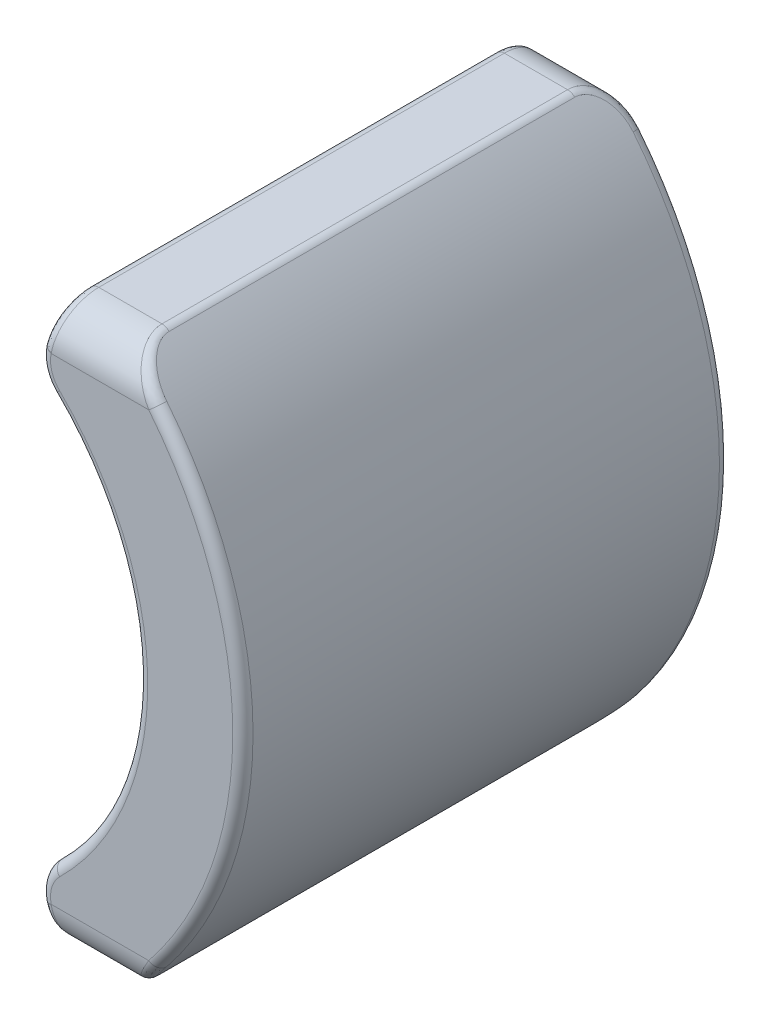
SolidWorks part; units mm, degrees
ref_plane "Front Plane" through (0, 0, 0) normal (0, 0, 1) x (1, 0, 0)
ref_plane "Top Plane" through (0, 0, 0) normal (0, 1, 0) x (1, 0, 0)
ref_plane "Right Plane" through (0, 0, 0) normal (1, 0, 0) x (0, 0, -1)
sketch "Sketch1" plane through (0, 0, 0) normal (0, 0, 1) x (1, 0, 0)
  line L0 (0, 0) -> (-9.63, 0) construction
  line L1 (-2.8919, -6.88) -> (-4.7519, -6.88)
  line L2 (-4.7519, -6.88) -> (-5.0982, -5.38)
  line L3 (-4.7519, 6.88) -> (-5.0982, 5.38)
  line L4 (-2.8919, 6.88) -> (-4.7519, 6.88)
  arc A0 (-2.8919, -6.88) -> (-2.8919, 6.88) centre (-9.63, 0) ccw
  arc A1 (-5.0982, 5.38) -> (-5.0982, -5.38) centre (-9.63, 0) cw
  point P6 (0, 0)
  dimension "D1" = 9.63
  dimension "D2" = 6.88
  dimension "D3" = 103
  dimension "D4" = 1.86
  dimension "D5" = 1.5
extrude "Boss-Extrude1" add sketch "Sketch1" along normal blind 12
fillet "Fillet1" radius 1 2 edges at (-5.0982, 5.38, 6) (-5.0982, -5.38, 6)
fillet "Fillet2" radius 1 4 edges at (-3.8219, 6.88, 0) (-3.8219, -6.88, 0) (-3.8219, -6.88, 12) (-3.8219, 6.88, 12)
fillet "Fillet3" radius 0.25 24 edges at (-4.9421, 5.4113, 12) (-4.8139, 6.6112, 11.6822) (-4.7519, 6.88, 6) (-4.8139, 6.6112, 0.3178) (-4.9421, 5.4113, 0) (-2.5957, 0, 0) (-4.9421, -5.4113, 0) (-4.8139, -6.6112, 0.3178) (-4.7519, -6.88, 6) (-4.8139, -6.6112, 11.6822) (-4.9421, -5.4113, 12) (-2.6418, -6.6258, 11.6661) (-2.8919, -6.88, 6) (-2.7615, -6.7498, 0.5066) (0, 0, 0) (-2.6418, 6.6258, 0.3339) (-2.8919, 6.88, 6) (-2.7615, 6.7498, 11.4934) (-2.5957, 0, 12) (0, 0, 12)
